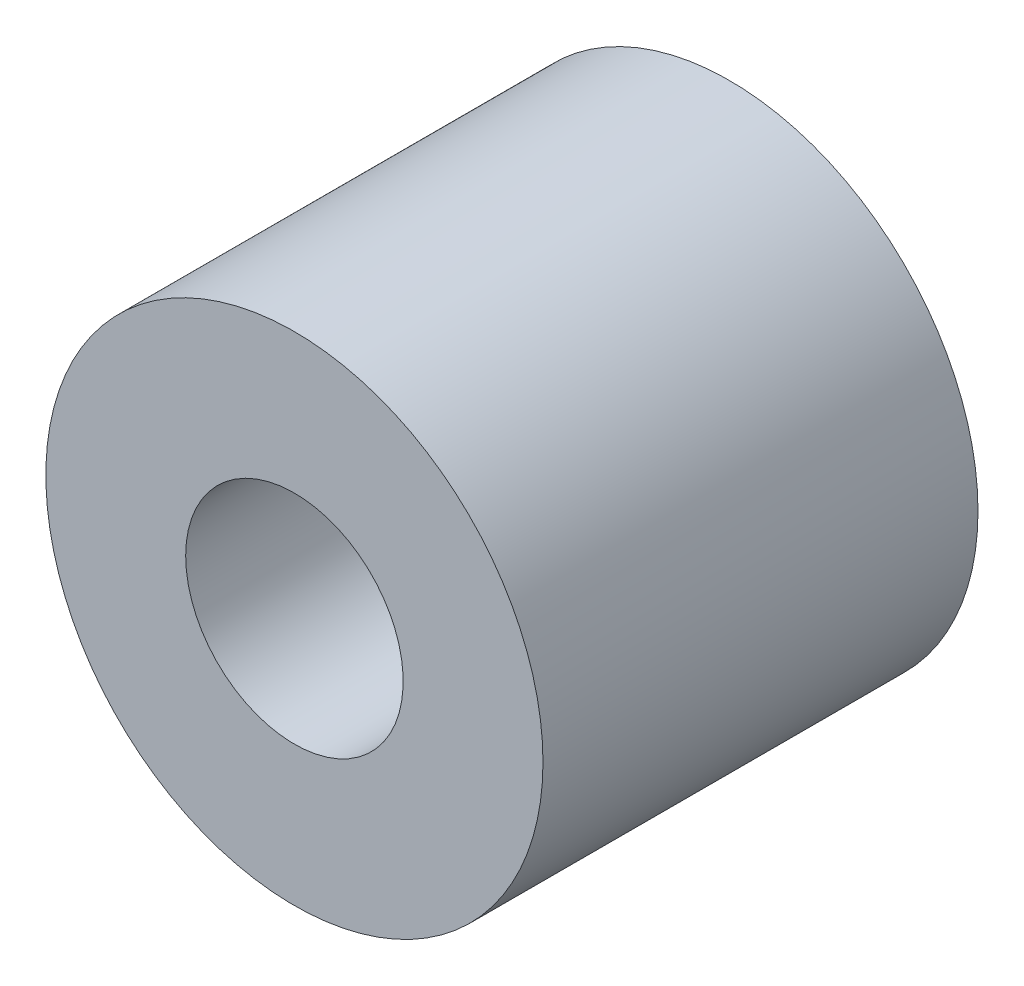
SolidWorks part; units mm, degrees
ref_plane "Plano frontal" through (0, 0, 0) normal (0, 0, 1) x (1, 0, 0)
ref_plane "Plano superior" through (0, 0, 0) normal (0, 1, 0) x (1, 0, 0)
ref_plane "Plano direito" through (0, 0, 0) normal (1, 0, 0) x (0, 0, -1)
sketch "Esboço1" plane through (0, 0, 0) normal (0, 0, 1) x (1, 0, 0)
  circle A0 centre (0, 0) radius 4
  dimension "D1" = 8
extrude "Ressalto-extrusão1" add sketch "Esboço1" along normal blind 7
sketch "Esboço2" plane through (0, 0, 0) normal (0, 0, -1) x (-1, 0, 0)
  circle A0 centre (0, 0) radius 1.75
  dimension "D1" = 3.5
extrude "Corte-extrusão1" cut sketch "Esboço2" against normal blind 7
